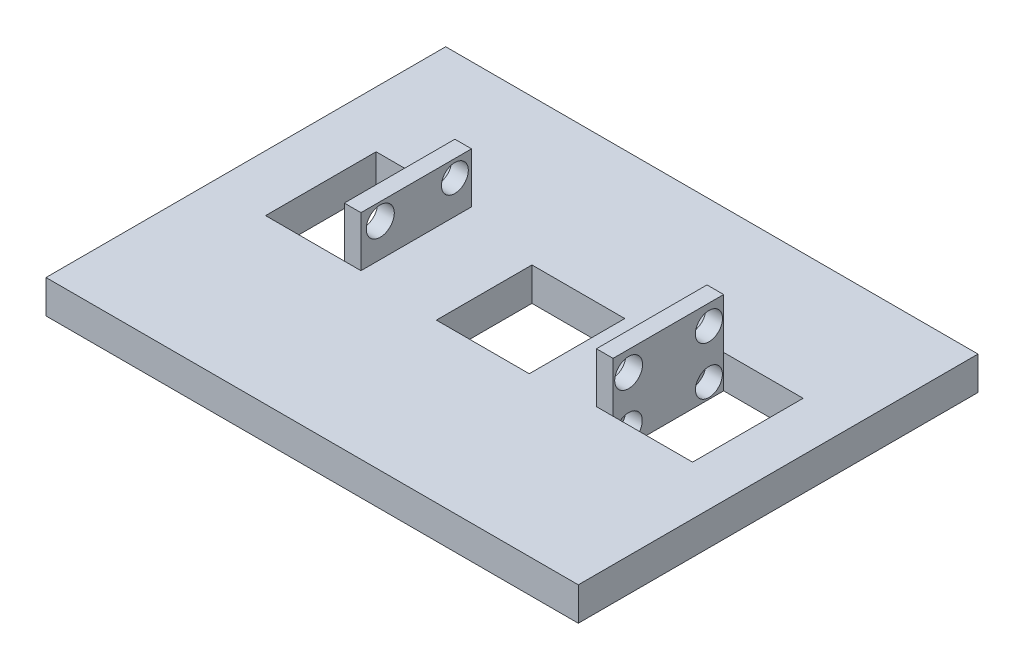
SolidWorks part; units mm, degrees
ref_plane "Front Plane" through (0, 0, 0) normal (0, 0, 1) x (1, 0, 0)
ref_plane "Top Plane" through (0, 0, 0) normal (0, 1, 0) x (1, 0, 0)
ref_plane "Right Plane" through (0, 0, 0) normal (1, 0, 0) x (0, 0, -1)
sketch "Sketch3" plane through (0, 0, 0) normal (0, 1, 0) x (1, 0, 0)
  line L0 (-45.5122, 37.7561) -> (-45.5122, -82.2439)
  line L1 (-45.5122, -82.2439) -> (114.2927, -82.2439)
  line L2 (114.2927, -82.2439) -> (114.2927, 37.7561)
  line L3 (114.2927, 37.7561) -> (-45.5122, 37.7561)
  dimension "D1" = 120
extrude "Boss-Extrude1" add sketch "Sketch3" along normal blind 10 contours L3 L0 L1 L2
sketch "Sketch4" plane through (0, 10, 0) normal (0, 1, 0) x (1, 0, 0)
  line L4 (52.0482, -16.006) -> (52.0482, -34.7217)
  line L5 (52.0482, -34.7217) -> (24.1653, -34.7217)
  line L6 (24.1653, -34.7217) -> (24.1653, -6.031)
  line L7 (24.1653, -6.031) -> (52.0482, -6.031)
  line L8 (52.0482, -6.031) -> (52.0482, -16.006)
extrude "Cut-Extrude1" cut sketch "Sketch4" against normal blind 20 contours L4 L5 L6 L7 L8
sketch "Sketch5" plane through (0, 10, 0) normal (0, 1, 0) x (1, 0, 0)
  circle A0 centre (84.2927, -22.2439) radius 3
  circle A1 centre (-15.5122, -22.2439) radius 3
  dimension "D3" = 6
  dimension "D4" = 6
extrude "Cut-Extrude3" cut sketch "Sketch5" against normal blind 16 and the other way blind 10 contours A1 | A0
sketch "Sketch7" plane through (0, 10, 0) normal (0, 1, 0) x (1, 0, 0)
  line L0 (-6.4035, -33.1965) -> (0, -33.1965)
  line L2 (70.6896, -33.1965) -> (77.3047, -33.1965)
  line L5 (-6.4035, -33.1965) -> (-28.6463, -33.1965)
  line L6 (-28.6463, -33.1965) -> (-28.6463, 0)
  line L7 (-28.6463, 0) -> (-6.4035, 0)
  line L10 (77.3047, 0) -> (99.5487, 0)
  line L11 (99.5487, 0) -> (99.5487, -33.1965)
  line L12 (99.5487, -33.1965) -> (77.3047, -33.1965)
  line L14 (0, -33.1965) -> (0, 0)
  line L15 (0, 0) -> (-6.4035, 0)
  line L16 (77.3047, 0) -> (70.6896, 0)
  line L17 (70.6896, 0) -> (70.6896, -33.1965)
extrude "Cut-Extrude6" cut sketch "Sketch7" against normal blind 10 contours L7 L15 L14 L0 L5 L6 | L2 L12 L11 L10 L16 L17
sketch "Sketch8" plane through (0, 0, 0) normal (-1, 0, 0) x (0, 0, 1)
  line L0 (0, 0) -> (0, 25.0892)
  line L3 (33.1965, 22.4658) -> (33.1965, 0)
  line L4 (33.1965, 0) -> (0, 0)
  line L5 (0, 25.0892) -> (33.1965, 25.0892)
  line L6 (33.1965, 25.0892) -> (33.1965, 22.4658)
  circle A0 centre (4.9993, 20.0098) radius 4.0274
  circle A1 centre (27.4009, 20.0098) radius 4.2056
  circle A2 centre (4.9993, 4.1937) radius 4.0395
  circle A3 centre (27.4009, 4.1937) radius 4.0362
extrude "Boss-Extrude3" add sketch "Sketch8" along normal blind 5
sketch "Sketch9" plane through (70.6896, 0, 0) normal (1, 0, 0) x (0, 0, -1)
  line L0 (-33.1965, 0) -> (-33.1965, 25.0562)
  line L1 (-33.1965, 25.0562) -> (0, 25.0562)
  line L2 (0, 25.0562) -> (0, 0)
  line L3 (0, 0) -> (-33.1965, 0)
  circle A0 centre (-28.524, 19.0414) radius 4.1806
  circle A1 centre (-4.4136, 19.0414) radius 4.0804
  circle A2 centre (-28.524, 4.5304) radius 4.0862
  circle A3 centre (-4.4136, 4.5304) radius 4.0366
extrude "Boss-Extrude4" add sketch "Sketch9" along normal blind 5
